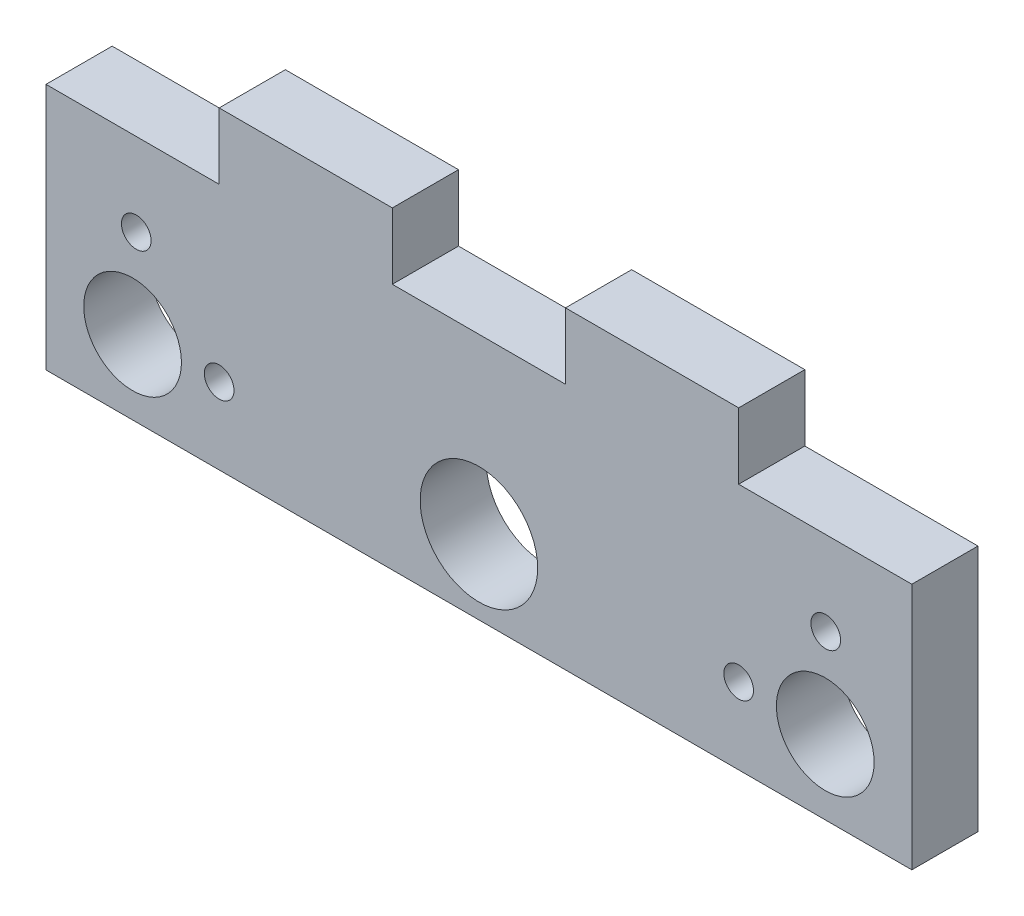
SolidWorks part; units mm, degrees
ref_plane "Front Plane" through (0, 0, 0) normal (0, 0, 1) x (1, 0, 0)
ref_plane "Top Plane" through (0, 0, 0) normal (0, 1, 0) x (1, 0, 0)
ref_plane "Right Plane" through (0, 0, 0) normal (1, 0, 0) x (0, 0, -1)
sketch "Model" plane through (0, 0, 0) normal (0, 0, 1) x (1, 0, 0)
  line L272 (0, 20) -> (0, 0)
  line L273 (14, 20) -> (0, 20)
  line L274 (14, 25.35) -> (14, 20)
  line L275 (28, 25.35) -> (14, 25.35)
  line L276 (28, 20) -> (28, 25.35)
  line L277 (42, 20) -> (28, 20)
  line L278 (42, 25.35) -> (42, 20)
  line L279 (56, 25.35) -> (42, 25.35)
  line L280 (56, 20) -> (56, 25.35)
  line L281 (70, 20) -> (56, 20)
  line L282 (70, 0) -> (70, 20)
  line L283 (0, 0) -> (70, 0)
  circle A18 centre (35, 6) radius 4.75
  circle A19 centre (63, 6) radius 3.95
  circle A20 centre (7, 6) radius 3.95
  circle A21 centre (14, 6.16) radius 1.2
  circle A22 centre (56, 6.16) radius 1.2
  circle A23 centre (63.04, 13.2) radius 1.2
  circle A24 centre (7.2981, 13.3) radius 1.2
extrude "Boss-Extrude1" add sketch "Model" along normal blind 5.35
